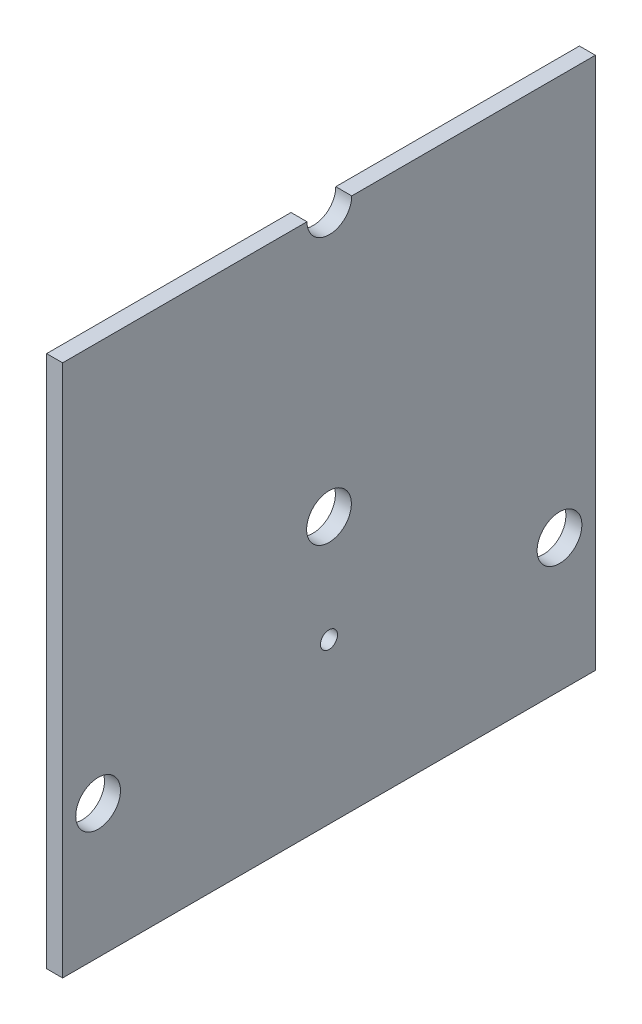
SolidWorks part; units mm, degrees
material "Tungsten"
ref_plane "Ebene vorne" through (0, 0, 0) normal (0, 0, 1) x (1, 0, 0)
ref_plane "Ebene oben" through (0, 0, 0) normal (0, 1, 0) x (1, 0, 0)
ref_plane "Ebene rechts" through (0, 0, 0) normal (1, 0, 0) x (0, 0, -1)
sketch "Sketch2" plane through (0, 0, 0) normal (1, 0, 0) x (0, 0, -1)
  line L0 (0, 50) -> (0, -50) construction
  line L1 (-50, 50) -> (50, 50)
  line L2 (-50, 50) -> (-50, -50)
  line L3 (-50, -50) -> (50, -50)
  line L4 (50, 50) -> (50, -50)
  line L5 (-50, 0) -> (50, 0) construction
  line L7 (-50, 50) -> (50, -50) construction
  circle A0 centre (0, 0) radius 4.2
  point P19 (0, 0)
  point P20 (0, 0)
  point P21 (0, 0)
  dimension "D3" = 8.4
  dimension "D1" = 100
  dimension "D2" = 100
extrude "Boss-Extrude1" add sketch "Sketch2" along normal blind 3
sketch "Sketch3" plane through (0, 0, 0) normal (-1, 0, 0) x (0, 0, 1)
  circle A0 centre (43.337, -24.9381) radius 4.2
  circle A1 centre (-43.2655, -25.0619) radius 4.2
  circle A2 centre (-0.0715, 49.9999) radius 4.2
  point P4 (43.337, -25.0619)
  point P9 (0, 0)
  dimension "D1" = 8.4
  dimension "D2" = 50
  dimension "D3" = 3
extrude "Cut-Extrude1" cut sketch "Sketch3" against normal blind 10
sketch "Sketch4" plane through (0, 0, 0) normal (-1, 0, 0) x (0, 0, 1)
  circle A0 centre (0, -20) radius 1.6
  point P2 (0, 0)
  dimension "D1" = 3.2
  dimension "D2" = 20
extrude "Cut-Extrude2" cut sketch "Sketch4" against normal blind 10
